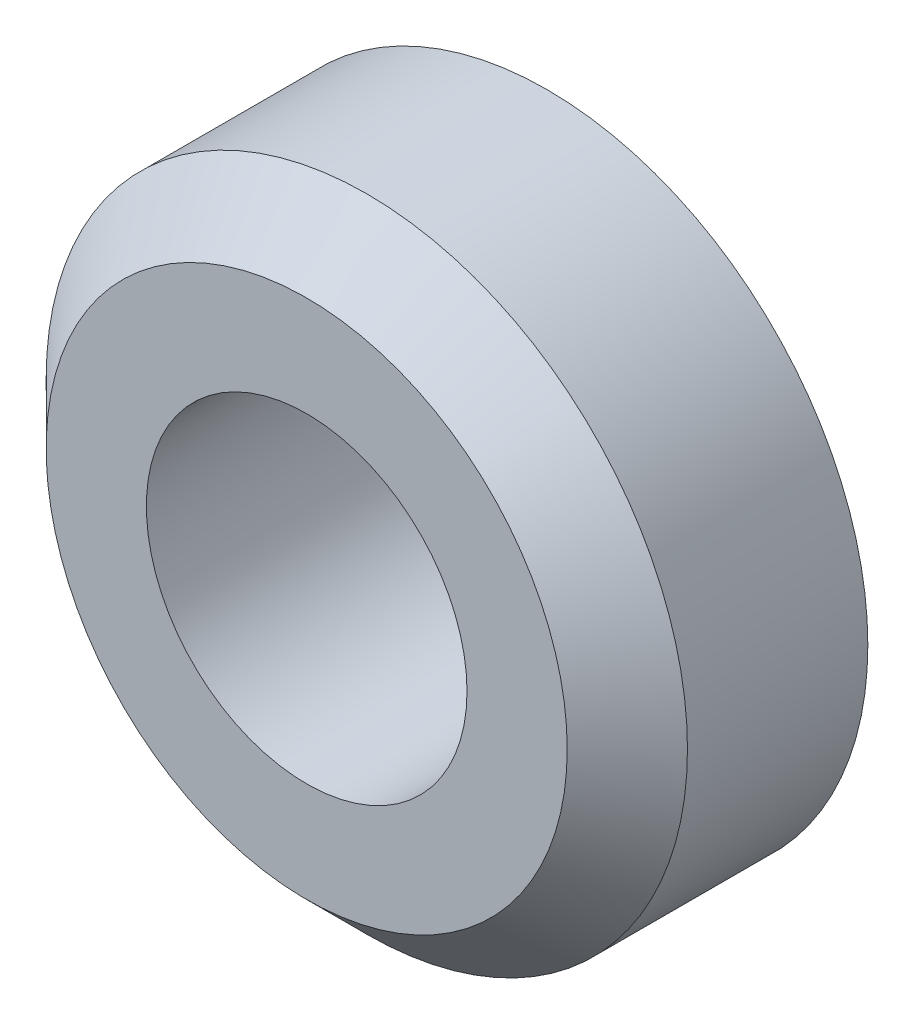
SolidWorks part; units mm, degrees
material "PEI"
ref_plane "Piano frontale" through (0, 0, 0) normal (0, 0, 1) x (1, 0, 0)
ref_plane "Piano superiore" through (0, 0, 0) normal (0, 1, 0) x (1, 0, 0)
ref_plane "Piano destro" through (0, 0, 0) normal (1, 0, 0) x (0, 0, -1)
sketch "Schizzo1" plane through (0, 0, 0) normal (0, 0, 1) x (1, 0, 0)
  circle A0 centre (0, 0) radius 4
  circle A1 centre (0, 0) radius 8
  dimension "D1" = 8
  dimension "D2" = 16
extrude "Estrusione-Estrusione1" add sketch "Schizzo1" along normal blind 6
chamfer "Smusso1" distance 1.5 angle 45 1 edges at (8, 0, 6)
